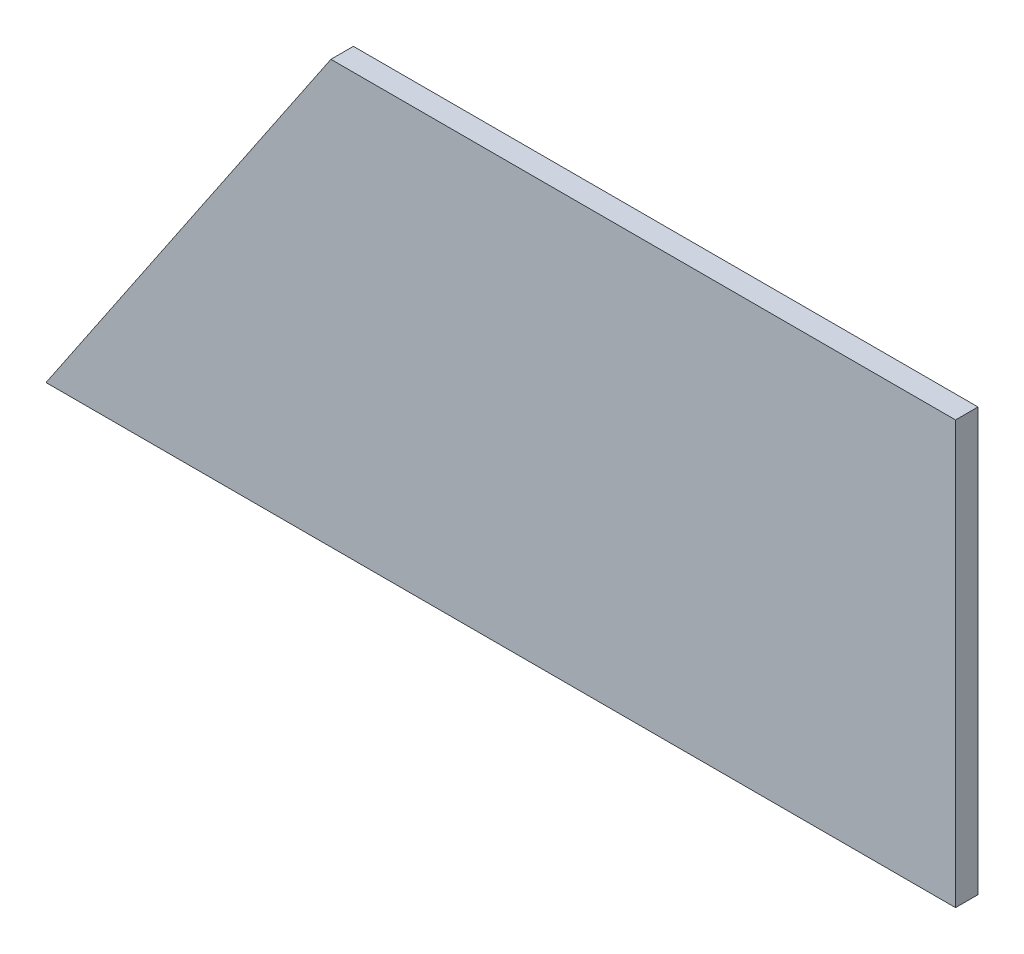
SolidWorks part; units mm, degrees
material "Acrylic (Medium-high impact)"
ref_plane "Front Plane" through (0, 0, 0) normal (0, 0, 1) x (1, 0, 0)
ref_plane "Top Plane" through (0, 0, 0) normal (0, 1, 0) x (1, 0, 0)
ref_plane "Right Plane" through (0, 0, 0) normal (1, 0, 0) x (0, 0, -1)
sketch "Sketch1" plane through (0, 0, 0) normal (0, 0, 1) x (1, 0, 0)
  line L0 (0, 0) -> (322.0913, 477.52)
  line L1 (322.0913, 477.52) -> (1028.2113, 477.52)
  line L2 (1028.2113, 477.52) -> (1028.2113, 0)
  line L3 (1028.2113, 0) -> (0, 0)
  dimension "D1" = 477.52
  dimension "D2" = 56
  dimension "D3" = 706.12
extrude "Boss-Extrude1" add sketch "Sketch1" along normal blind 25.4
